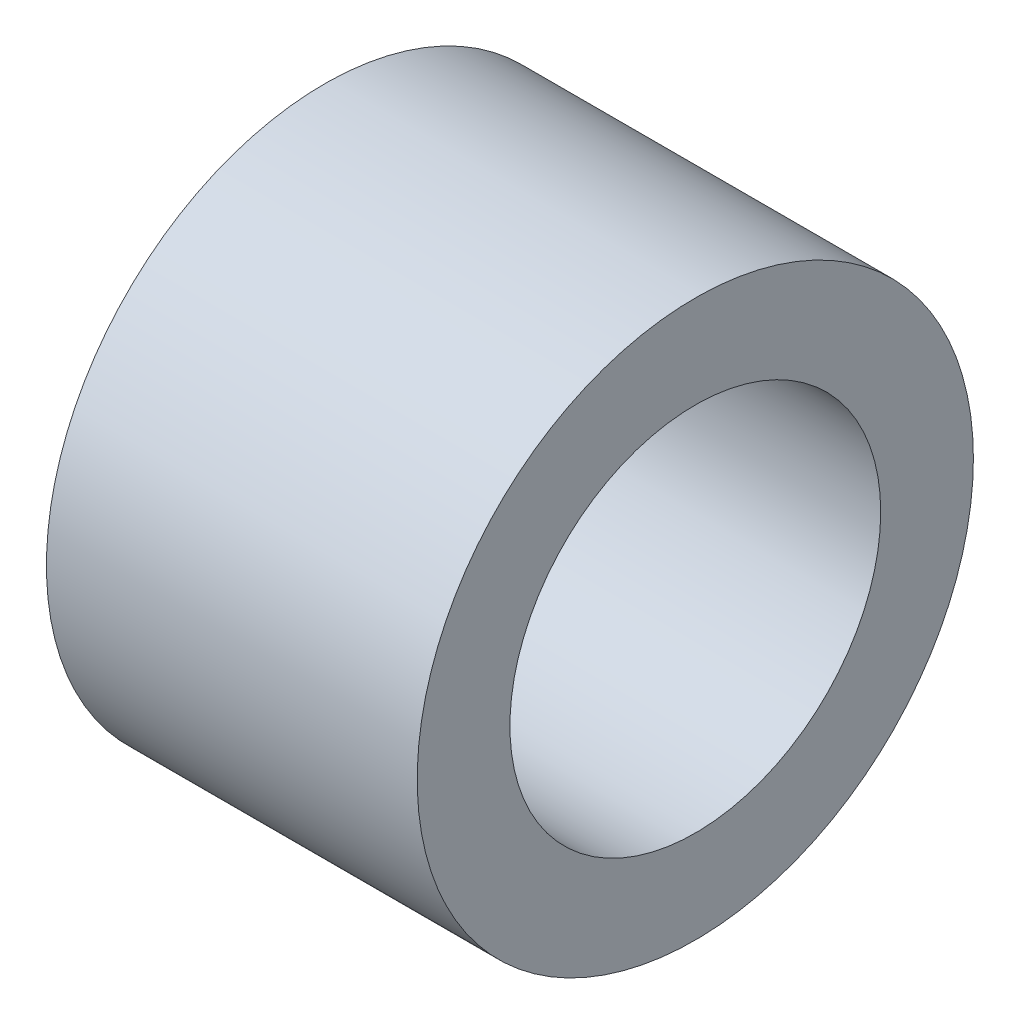
SolidWorks part; units mm, degrees
ref_plane "Front Plane" through (0, 0, 0) normal (0, 0, 1) x (1, 0, 0)
ref_plane "Top Plane" through (0, 0, 0) normal (0, 1, 0) x (1, 0, 0)
ref_plane "Right Plane" through (0, 0, 0) normal (1, 0, 0) x (0, 0, -1)
sketch "Sketch2" plane through (0, 0, 0) normal (1, 0, 0) x (0, 0, -1)
  circle A0 centre (0, 0) radius 10
  circle A1 centre (0, 0) radius 15
  dimension "D1" = 20
  dimension "D2" = 30
extrude "Boss-Extrude1" add sketch "Sketch2" along normal blind 20
